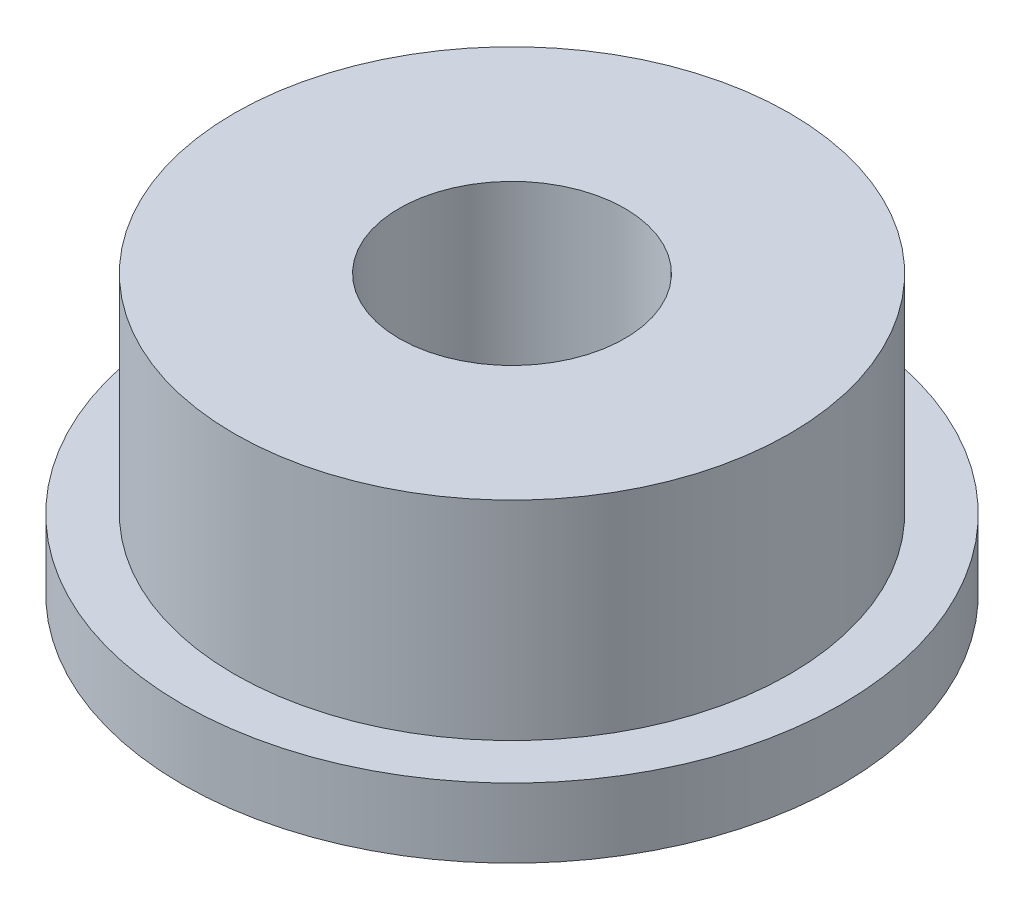
SolidWorks part; units mm, degrees
ref_plane "Front Plane" through (0, 0, 0) normal (0, 0, 1) x (1, 0, 0)
ref_plane "Top Plane" through (0, 0, 0) normal (0, 1, 0) x (1, 0, 0)
ref_plane "Right Plane" through (0, 0, 0) normal (1, 0, 0) x (0, 0, -1)
sketch "Sketch1" plane through (0, 0, 0) normal (0, 1, 0) x (1, 0, 0)
  circle A0 centre (0, 0) radius 1.625
  circle A1 centre (0, 0) radius 4.75
  dimension "D1" = 3.25
  dimension "D2" = 9.5
extrude "Boss-Extrude1" add sketch "Sketch1" along normal blind 1
sketch "Sketch2" plane through (0, 1, 0) normal (0, 1, 0) x (1, 0, 0)
  circle A0 centre (0, 0) radius 4
  circle A1 centre (0, 0) radius 1.625
  circle A2 centre (0, 0) radius 1.625 construction
  dimension "D1" = 8
extrude "Boss-Extrude2" add sketch "Sketch2" along normal offset from surface (3 mm away) 4 up to face at (0, 0, 4.75)
